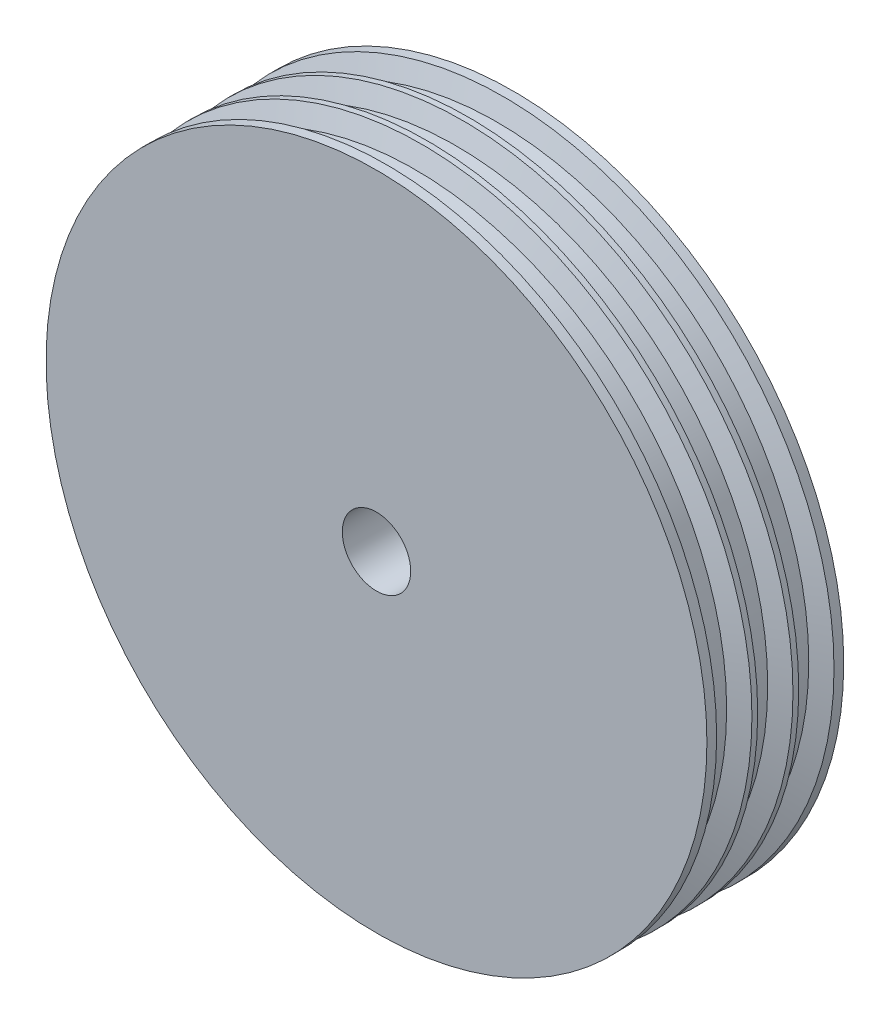
SolidWorks part; units mm, degrees
ref_plane "前视基准面" through (0, 0, 0) normal (0, 0, 1) x (1, 0, 0)
ref_plane "上视基准面" through (0, 0, 0) normal (0, 1, 0) x (1, 0, 0)
ref_plane "右视基准面" through (0, 0, 0) normal (1, 0, 0) x (0, 0, -1)
other "Configuration Table"
sketch "草图2" plane through (0, 0, 0) normal (1, 0, 0) x (0, 0, -1)
  line L0 (0, 0) -> (50, 0) construction
  line L1 (0, 0) -> (0, 12.5) construction
  line L2 (0, 12.5) -> (50, 12.5)
  line L3 (0, 120.75) -> (0, 12.5)
  line L4 (0, 120.75) -> (3.5531, 120.75)
  line L5 (50, 120.75) -> (50, 12.5)
  line L7 (5.9183, 113.8811) -> (14.0817, 113.8811)
  line L8 (5.9183, 113.8811) -> (3.5531, 120.75)
  line L9 (14.0817, 113.8811) -> (16.4469, 120.75)
  line L11 (20.9183, 113.8811) -> (18.5531, 120.75)
  line L12 (20.9183, 113.8811) -> (29.0817, 113.8811)
  line L13 (29.0817, 113.8811) -> (31.4469, 120.75)
  line L14 (35.9183, 113.8811) -> (33.5531, 120.75)
  line L15 (35.9183, 113.8811) -> (44.0817, 113.8811)
  line L16 (44.0817, 113.8811) -> (46.4469, 120.75)
  line L17 (16.4469, 120.75) -> (18.5531, 120.75)
  line L18 (31.4469, 120.75) -> (33.5531, 120.75)
  line L19 (46.4469, 120.75) -> (50, 120.75)
  dimension "D1" = 3
revolve "旋转1" add sketch "草图2" angle 360 about L0
